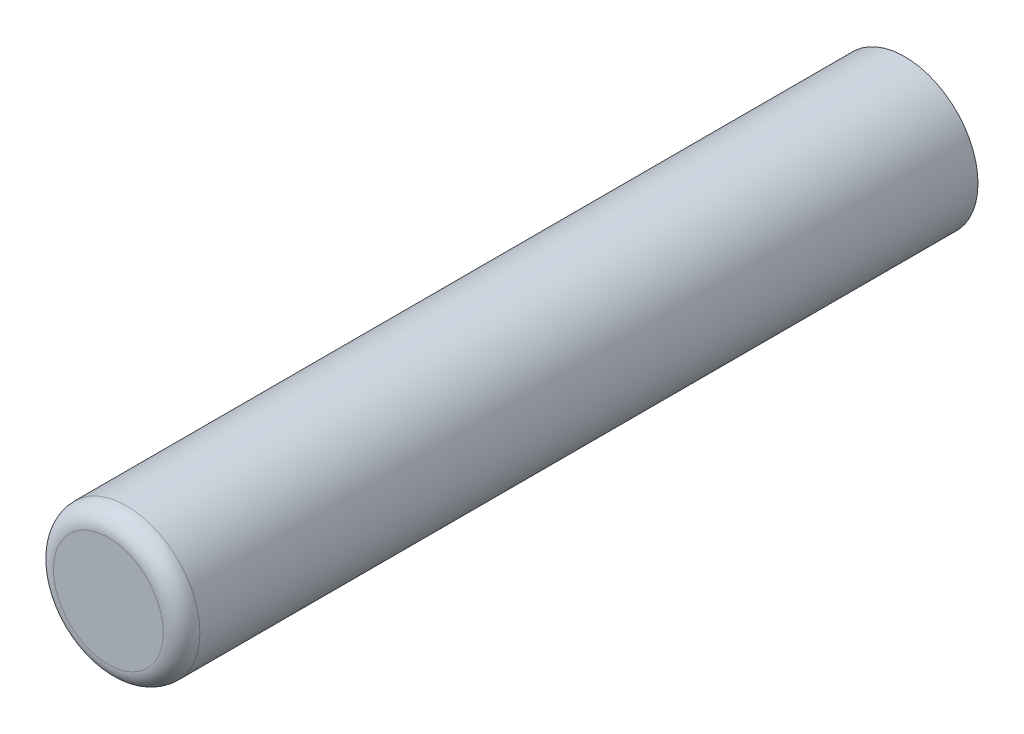
SolidWorks part; units mm, degrees
ref_plane "Alzado" through (0, 0, 0) normal (0, 0, 1) x (1, 0, 0)
ref_plane "Planta" through (0, 0, 0) normal (0, 1, 0) x (1, 0, 0)
ref_plane "Vista lateral" through (0, 0, 0) normal (1, 0, 0) x (0, 0, -1)
sketch "Croquis1" plane through (0, 0, 0) normal (0, 0, 1) x (1, 0, 0)
  circle A0 centre (0, 0) radius 8
  dimension "D1" = 16
extrude "Saliente-Extruir1" add sketch "Croquis1" along normal blind 87
fillet "Redondeo1" radius 2 1 edges at (8, 0, 87)
sketch "Croquis3" plane through (0, 0, 0) normal (0, 0, -1) x (-1, 0, 0)
  circle A0 centre (0, 0) radius 5
  dimension "D1" = 10
extrude "Cortar-Extruir1" cut sketch "Croquis3" against normal blind 25
